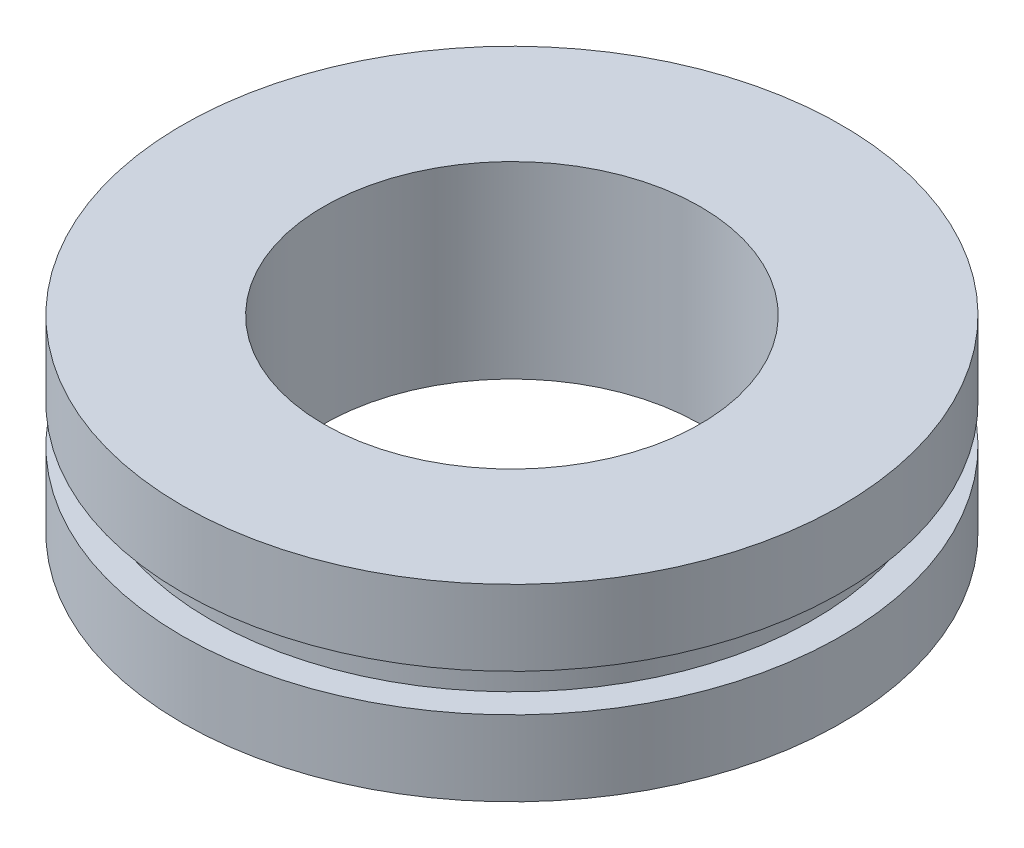
SolidWorks part; units mm, degrees
ref_plane "前视基准面" through (0, 0, 0) normal (0, 0, 1) x (1, 0, 0)
ref_plane "上视基准面" through (0, 0, 0) normal (0, 1, 0) x (1, 0, 0)
ref_plane "右视基准面" through (0, 0, 0) normal (1, 0, 0) x (0, 0, -1)
other "Configuration Table"
sketch "草图1" plane through (0, 0, 0) normal (0, 1, 0) x (1, 0, 0)
  circle A0 centre (0, 0) radius 10
  circle A1 centre (0, 0) radius 17.5
  point P5 (0, -0.2104)
  dimension "D1" = 20
  dimension "D2" = 35
extrude "凸台-拉伸1" add sketch "草图1" along normal blind 10
ref_plane "基准面2" through (0, 5, 0) normal (0, 1, 0) x (1, 0, 0)
sketch "草图4" plane through (0, 5, 0) normal (0, 1, 0) x (1, 0, 0)
  circle A0 centre (0, 0) radius 17.5
  circle A1 centre (0, 0) radius 16
  dimension "D1" = 32
extrude "切除-拉伸1" cut sketch "草图4" against normal mid plane 2
